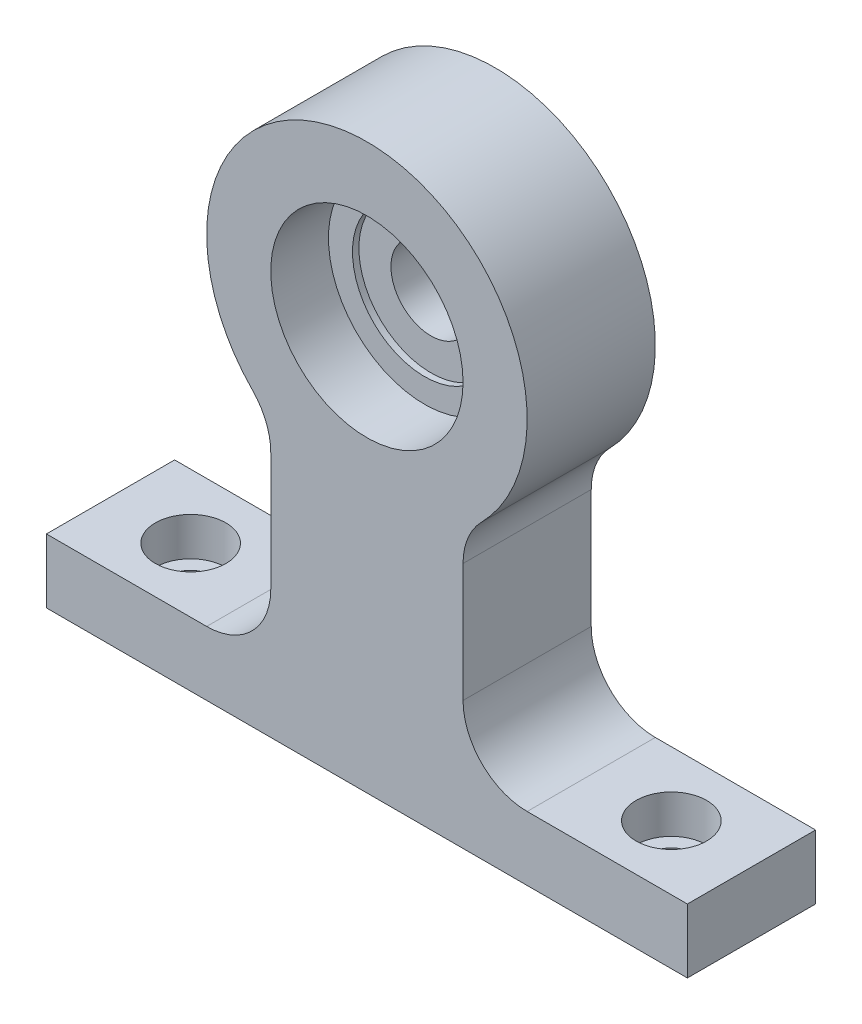
SolidWorks part; units mm, degrees
ref_plane "Front Plane" through (0, 0, 0) normal (0, 0, 1) x (1, 0, 0)
ref_plane "Top Plane" through (0, 0, 0) normal (0, 1, 0) x (1, 0, 0)
ref_plane "Right Plane" through (0, 0, 0) normal (1, 0, 0) x (0, 0, -1)
sketch "Sketch1" plane through (0, 0, 0) normal (0, 0, 1) x (1, 0, 0)
  line L0 (15, 43) -> (15, 10)
  line L1 (-50, 0) -> (50, 0)
  line L2 (-50, 0) -> (-50, 10)
  line L3 (-50, 10) -> (-15, 10)
  line L4 (50, 0) -> (50, 10)
  line L5 (-15, 43) -> (-15, 10)
  line L6 (0, 0) -> (0, 63) construction
  line L7 (15, 10) -> (50, 10)
  circle A0 centre (0, 63) radius 15
  arc A1 (15, 43) -> (-15, 43) centre (0, 63) ccw
  circle A2 centre (0, 63) radius 25 construction
  point P4 (0, 0)
  point P15 (15.1237, 38.0934)
  dimension "D1" = 30
  dimension "D3" = 63
  dimension "D4" = 100
  dimension "D5" = 10
  dimension "D2" = 10
extrude "Boss-Extrude1" add sketch "Sketch1" along normal mid plane 20
sketch "Sketch2" plane through (0, 0, 0) normal (0, 0, 1) x (1, 0, 0)
  circle A0 centre (0, 63) radius 15 construction
  circle A1 centre (0, 63) radius 15
  circle A2 centre (0, 63) radius 6.25
  dimension "D1" = 12.5
extrude "Boss-Extrude2" add sketch "Sketch2" against normal through all
fillet "Fillet1" radius 10 4 edges at (15, 43, 0) (-15, 43, 0) (-15, 10, 0) (15, 10, 0)
hole_wizard "CBORE for M6 SHCS1" positions "Sketch3" profile "Sketch4" counterbore size "M6" standard "ANSI Metric" end condition through all
sketch "Sketch3" plane through (0, 10, 0) normal (0, 1, 0) x (1, 0, 0)
  line L0 (-37.5, 0) -> (37.5, 0)
  point P0 (-37.5, 0)
  point P2 (37.5, 0)
  dimension "D1" = 75
sketch "Sketch4" plane through (-37.5, 10, 0) normal (1, 0, 0) x (0, 0, 1)
  line L0 (0, 0) -> (0, 10)
  line L1 (0, 10) -> (3.3, 10)
  line L3 (3.3, 10) -> (3.3, 6)
  line L4 (3.3, 6) -> (5.5, 6)
  line L5 (5.5, 6) -> (5.5, 0)
  line L7 (5.5, 0) -> (0, 0)
  line L11 (0, -6.35) -> (0, 107.95) construction
  dimension "Thru Hole Dia." = 6.6
  dimension "Thru Hole Depth" = 10
  dimension "C'Bore Dia." = 11
  dimension "C'Bore Depth" = 6
sketch "Sketch5" plane through (0, 0, 0) normal (0, 0, 1) x (1, 0, 0)
  circle A0 centre (0, 63) radius 11.25
  circle A1 centre (0, 63) radius 15 construction
  circle A2 centre (0, 63) radius 15
  dimension "D1" = 22.5
extrude "Boss-Extrude3" add sketch "Sketch5" along normal blind 1
